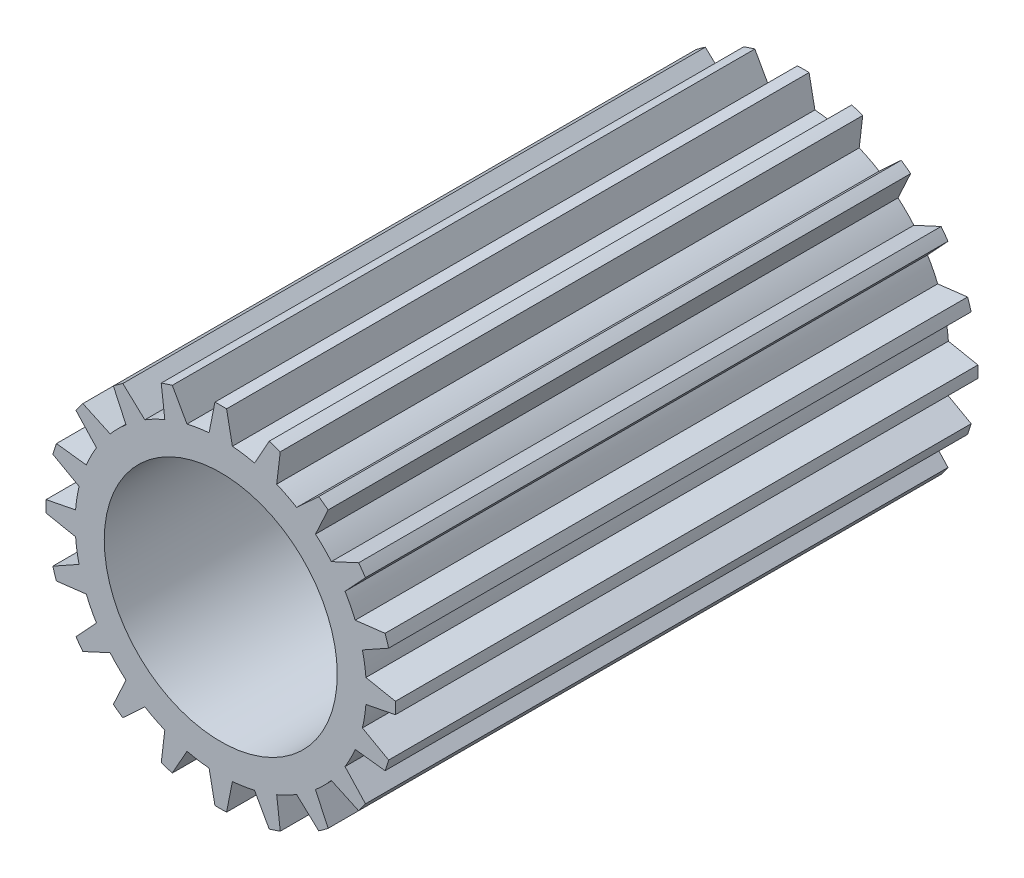
SolidWorks part; units mm, degrees
ref_plane "Front Plane" through (0, 0, 0) normal (0, 0, 1) x (1, 0, 0)
ref_plane "Top Plane" through (0, 0, 0) normal (0, 1, 0) x (1, 0, 0)
ref_plane "Right Plane" through (0, 0, 0) normal (1, 0, 0) x (0, 0, -1)
sketch "Sketch1" plane through (0, 0, 0) normal (0, 0, 1) x (1, 0, 0)
  line L0 (0, 0) -> (50000, 0) construction
  line L1 (0, -1000) -> (0, 49000) construction
  line L2 (-0.5, 14.9917) -> (-1, 12.4599)
  line L3 (0.5, 14.9917) -> (1, 12.4599)
  line L4 (4.1572, 14.4124) -> (2.8993, 12.1591)
  line L5 (5.1082, 14.1034) -> (4.8014, 11.5411)
  line L6 (8.4074, 12.4224) -> (6.5147, 10.6681)
  line L7 (9.2164, 11.8346) -> (8.1328, 9.4925)
  line L8 (11.8346, 9.2164) -> (9.4925, 8.1328)
  line L9 (12.4224, 8.4074) -> (10.6681, 6.5147)
  line L10 (14.1034, 5.1082) -> (11.5411, 4.8014)
  line L11 (14.4124, 4.1572) -> (12.1591, 2.8993)
  line L12 (14.9917, 0.5) -> (12.4599, 1)
  line L13 (14.9917, -0.5) -> (12.4599, -1)
  line L14 (14.4124, -4.1572) -> (12.1591, -2.8993)
  line L15 (14.1034, -5.1082) -> (11.5411, -4.8014)
  line L16 (12.4224, -8.4074) -> (10.6681, -6.5147)
  line L17 (11.8346, -9.2164) -> (9.4925, -8.1328)
  line L18 (9.2164, -11.8346) -> (8.1328, -9.4925)
  line L19 (8.4074, -12.4224) -> (6.5147, -10.6681)
  line L20 (5.1082, -14.1034) -> (4.8014, -11.5411)
  line L21 (4.1572, -14.4124) -> (2.8993, -12.1591)
  line L22 (0.5, -14.9917) -> (1, -12.4599)
  line L23 (-0.5, -14.9917) -> (-1, -12.4599)
  line L24 (-4.1572, -14.4124) -> (-2.8993, -12.1591)
  line L25 (-5.1082, -14.1034) -> (-4.8014, -11.5411)
  line L26 (-8.4074, -12.4224) -> (-6.5147, -10.6681)
  line L27 (-9.2164, -11.8346) -> (-8.1328, -9.4925)
  line L28 (-11.8346, -9.2164) -> (-9.4925, -8.1328)
  line L29 (-12.4224, -8.4074) -> (-10.6681, -6.5147)
  line L30 (-14.1034, -5.1082) -> (-11.5411, -4.8014)
  line L31 (-14.4124, -4.1572) -> (-12.1591, -2.8993)
  line L32 (-14.9917, -0.5) -> (-12.4599, -1)
  line L33 (-14.9917, 0.5) -> (-12.4599, 1)
  line L34 (-14.4124, 4.1572) -> (-12.1591, 2.8993)
  line L35 (-14.1034, 5.1082) -> (-11.5411, 4.8014)
  line L36 (-12.4224, 8.4074) -> (-10.6681, 6.5147)
  line L37 (-11.8346, 9.2164) -> (-9.4925, 8.1328)
  line L38 (-9.2164, 11.8346) -> (-8.1328, 9.4925)
  line L39 (-8.4074, 12.4224) -> (-6.5147, 10.6681)
  line L40 (-5.1082, 14.1034) -> (-4.8014, 11.5411)
  line L41 (-4.1572, 14.4124) -> (-2.8993, 12.1591)
  circle A0 centre (0, 0) radius 10
  arc A1 (-8.1328, 9.4925) -> (-9.4925, 8.1328) centre (0, 0) ccw
  arc A2 (-4.1572, 14.4124) -> (-5.1082, 14.1034) centre (0, 0) ccw
  arc A3 (-8.4074, 12.4224) -> (-9.2164, 11.8346) centre (0, 0) ccw
  arc A4 (-11.8346, 9.2164) -> (-12.4224, 8.4074) centre (0, 0) ccw
  arc A5 (-14.1034, 5.1082) -> (-14.4124, 4.1572) centre (0, 0) ccw
  arc A6 (-14.9917, 0.5) -> (-14.9917, -0.5) centre (0, 0) ccw
  arc A7 (-14.4124, -4.1572) -> (-14.1034, -5.1082) centre (0, 0) ccw
  arc A8 (0.5, 14.9917) -> (-0.5, 14.9917) centre (0, 0) ccw
  arc A9 (5.1082, 14.1034) -> (4.1572, 14.4124) centre (0, 0) ccw
  arc A10 (9.2164, 11.8346) -> (8.4074, 12.4224) centre (0, 0) ccw
  arc A11 (12.4224, 8.4074) -> (11.8346, 9.2164) centre (0, 0) ccw
  arc A12 (14.4124, 4.1572) -> (14.1034, 5.1082) centre (0, 0) ccw
  arc A13 (14.9917, -0.5) -> (14.9917, 0.5) centre (0, 0) ccw
  arc A14 (14.1034, -5.1082) -> (14.4124, -4.1572) centre (0, 0) ccw
  arc A15 (11.8346, -9.2164) -> (12.4224, -8.4074) centre (0, 0) ccw
  arc A16 (8.4074, -12.4224) -> (9.2164, -11.8346) centre (0, 0) ccw
  arc A17 (4.1572, -14.4124) -> (5.1082, -14.1034) centre (0, 0) ccw
  arc A18 (-0.5, -14.9917) -> (0.5, -14.9917) centre (0, 0) ccw
  arc A19 (-5.1082, -14.1034) -> (-4.1572, -14.4124) centre (0, 0) ccw
  arc A20 (-9.2164, -11.8346) -> (-8.4074, -12.4224) centre (0, 0) ccw
  arc A21 (-12.4224, -8.4074) -> (-11.8346, -9.2164) centre (0, 0) ccw
  arc A22 (-4.8014, 11.5411) -> (-6.5147, 10.6681) centre (0, 0) ccw
  arc A23 (-1, 12.4599) -> (-2.8993, 12.1591) centre (0, 0) ccw
  arc A24 (2.8993, 12.1591) -> (1, 12.4599) centre (0, 0) ccw
  arc A25 (6.5147, 10.6681) -> (4.8014, 11.5411) centre (0, 0) ccw
  arc A26 (9.4925, 8.1328) -> (8.1328, 9.4925) centre (0, 0) ccw
  arc A27 (11.5411, 4.8014) -> (10.6681, 6.5147) centre (0, 0) ccw
  arc A28 (12.4599, 1) -> (12.1591, 2.8993) centre (0, 0) ccw
  arc A29 (12.1591, -2.8993) -> (12.4599, -1) centre (0, 0) ccw
  arc A30 (10.6681, -6.5147) -> (11.5411, -4.8014) centre (0, 0) ccw
  arc A31 (8.1328, -9.4925) -> (9.4925, -8.1328) centre (0, 0) ccw
  arc A32 (4.8014, -11.5411) -> (6.5147, -10.6681) centre (0, 0) ccw
  arc A33 (1, -12.4599) -> (2.8993, -12.1591) centre (0, 0) ccw
  arc A34 (-2.8993, -12.1591) -> (-1, -12.4599) centre (0, 0) ccw
  arc A35 (-6.5147, -10.6681) -> (-4.8014, -11.5411) centre (0, 0) ccw
  arc A36 (-9.4925, -8.1328) -> (-8.1328, -9.4925) centre (0, 0) ccw
  arc A37 (-11.5411, -4.8014) -> (-10.6681, -6.5147) centre (0, 0) ccw
  arc A38 (-12.4599, -1) -> (-12.1591, -2.8993) centre (0, 0) ccw
  arc A39 (-12.1591, 2.8993) -> (-12.4599, 1) centre (0, 0) ccw
  arc A40 (-10.6681, 6.5147) -> (-11.5411, 4.8014) centre (0, 0) ccw
  point P91 (0, 0)
  dimension "D1" = 20
  dimension "D2" = 25
  dimension "D3" = 30
  dimension "D4" = 1
  dimension "D5" = 2
  dimension "D6" = 20
extrude "Boss-Extrude1" add sketch "Sketch1" along normal mid plane 50
